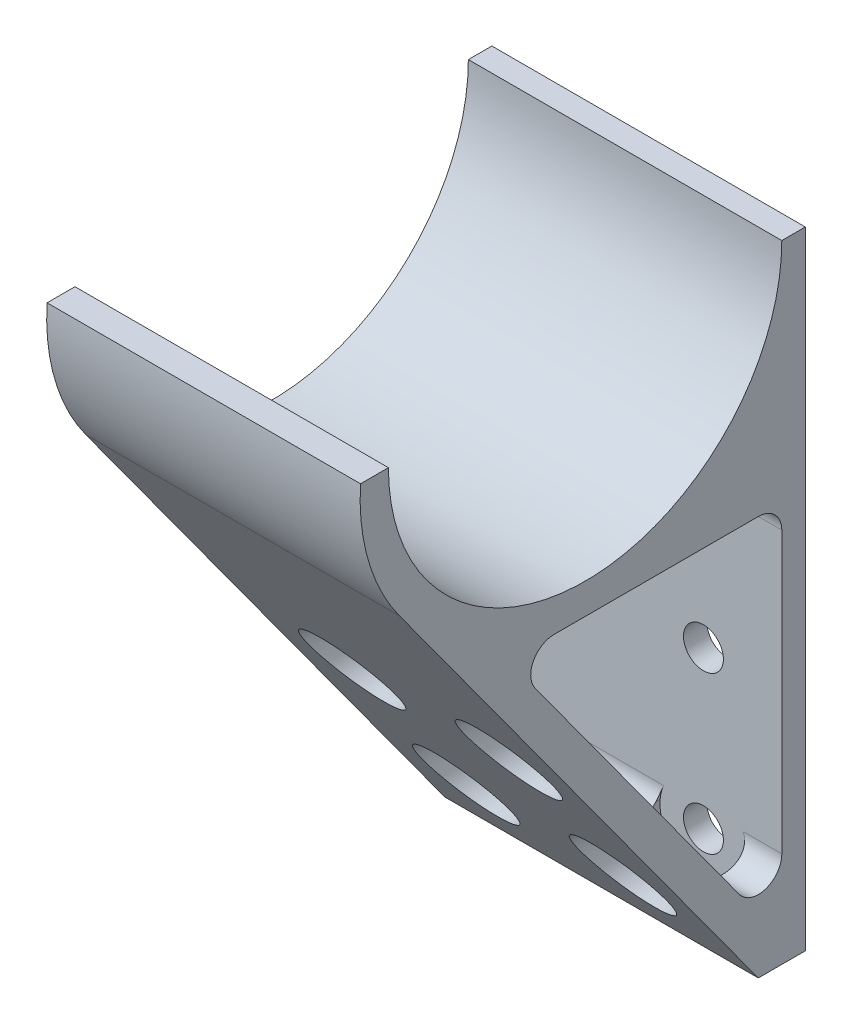
SolidWorks part; units mm, degrees
ref_plane "Спереди" through (0, 0, 0) normal (0, 0, 1) x (1, 0, 0)
ref_plane "Сверху" through (0, 0, 0) normal (0, 1, 0) x (1, 0, 0)
ref_plane "Справа" through (0, 0, 0) normal (1, 0, 0) x (0, 0, -1)
sketch "Эскиз1" plane through (0, 0, 0) normal (1, 0, 0) x (0, 0, -1)
  line L0 (0, 0) -> (0, -80)
  line L1 (0, 0) -> (-3, 0)
  line L2 (-3, 0) -> (-77.8373, 0) construction
  line L3 (-53.2, 0) -> (-56.7604, 0)
  line L4 (0, -80) -> (-6, -80)
  line L5 (-6, -80) -> (-51.794, -17.0803)
  line L7 (-3, -32) -> (-3, -67.78)
  line L10 (-8.4256, -69.5454) -> (-34.4668, -33.7654)
  line L11 (-32.0413, -29) -> (-6, -29)
  arc A0 (-3, 0) -> (-53.2, 0) centre (-28.1, 0) cw
  arc A1 (-56.7604, 0) -> (-51.794, -17.0803) centre (-30.6015, -1.656) ccw
  arc A2 (-3, -67.78) -> (-8.4256, -69.5454) centre (-6, -67.78) cw
  arc A3 (-6, -29) -> (-3, -32) centre (-6, -32) cw
  arc A4 (-34.4668, -33.7654) -> (-32.0413, -29) centre (-32.0413, -32) cw
  point P16 (-3, -77)
  dimension "D3" = 6
  dimension "D4" = 3
  dimension "D7" = 3
  dimension "D1" = 80
  dimension "D2" = 3
  dimension "D5" = 3
  dimension "D6" = 3
extrude "Бобышка-Вытянуть1" add sketch "Эскиз1" along normal blind 40
sketch "Эскиз2" plane through (0, 0, 0) normal (0, 0, -1) x (-1, 0, 0)
  line L0 (-44.7022, -70) -> (3.7377, -70) construction
  line L1 (-40, -80) -> (0, -80) construction
  line L2 (-45.5596, -50) -> (11.4538, -50) construction
  line L3 (-40, -80) -> (-40, 0) construction
  circle A0 centre (-30, -50) radius 2.55
  circle A1 centre (-10, -50) radius 2.55
  circle A2 centre (-10, -70) radius 2.55
  circle A3 centre (-30, -70) radius 2.55
  dimension "D3" = 5.1
  dimension "D4" = 5.1
  dimension "D5" = 5.1
  dimension "D6" = 5.1
  dimension "D8" = 5.1
  dimension "D9" = 10
  dimension "D10" = 20
  dimension "D11" = 20
  dimension "D1" = 10
  dimension "D2" = 20
  dimension "D7" = 10
extrude "Вырез-Вытянуть1" cut sketch "Эскиз2" against normal through all
ref_plane "Плоскость1" through (0, 0, 3) normal (0, 0, 1) x (1, 0, 0)
sketch "Эскиз3" plane through (0, 0, 3) normal (0, 0, 1) x (1, 0, 0)
  circle A0 centre (30, -50) radius 2.55 construction
  circle A1 centre (30, -50) radius 2.55
  circle A2 centre (10, -50) radius 2.55 construction
  circle A3 centre (10, -50) radius 2.55
  circle A4 centre (10, -70) radius 2.55 construction
  circle A5 centre (10, -70) radius 2.55
  circle A6 centre (30, -70) radius 2.55 construction
  circle A7 centre (30, -70) radius 2.55
  circle A8 centre (10, -50) radius 5.55
  circle A9 centre (30, -50) radius 5.55
  circle A10 centre (10, -70) radius 5.55
  circle A11 centre (30, -70) radius 5.55
  dimension "D1" = 3
  dimension "D2" = 3
  dimension "D3" = 3
  dimension "D4" = 3
extrude "Вырез-Вытянуть2" cut sketch "Эскиз3" along normal up to surface (24.8345 mm away)
